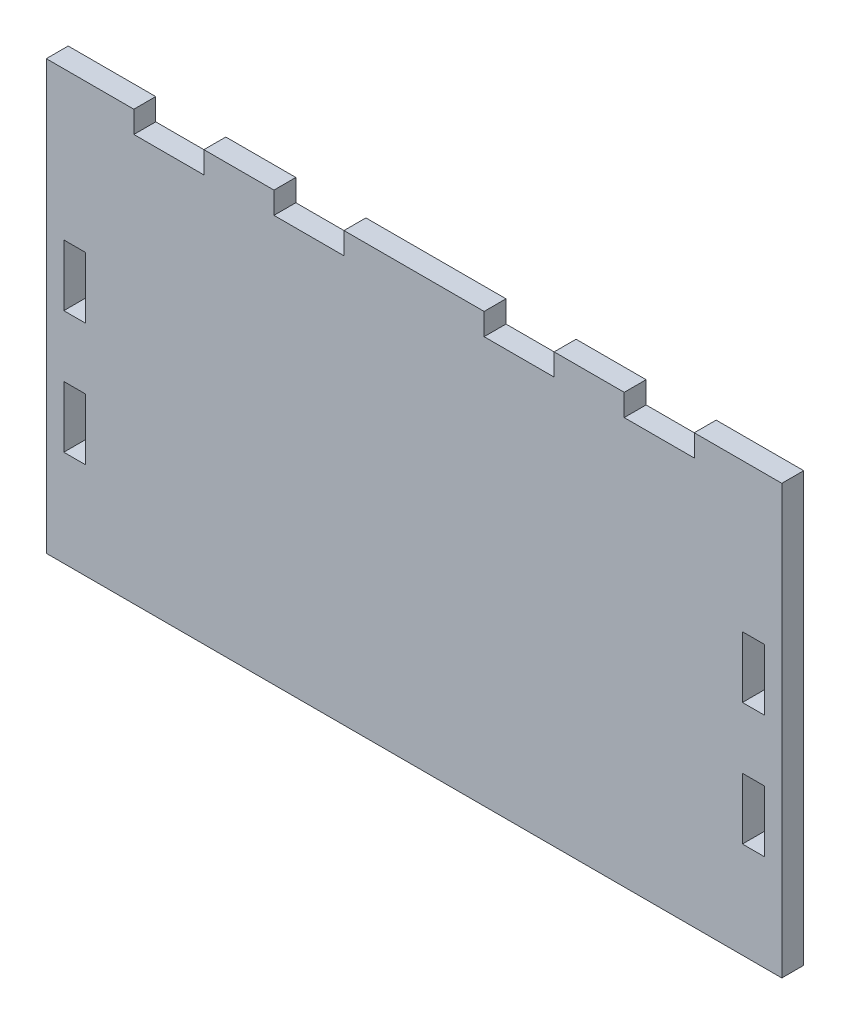
SolidWorks part; units mm, degrees
material "Beech"
ref_plane "Front" through (0, 0, 0) normal (0, 0, 1) x (1, 0, 0)
ref_plane "Top" through (0, 0, 0) normal (0, 1, 0) x (1, 0, 0)
ref_plane "Right" through (0, 0, 0) normal (1, 0, 0) x (0, 0, -1)
sketch "Sketch1" plane through (0, 0, 0) normal (0, 0, 1) x (1, 0, 0)
  line L0 (-42, -24.4632) -> (0, -24.4632) construction
  line L1 (-42, -24.4632) -> (-42, 24.4632) construction
  line L2 (0, -24.4632) -> (0, 24.4632) construction
  line L3 (-42, 24.4632) -> (0, 24.4632) construction
  line L4 (-42, -24.4632) -> (0, 24.4632) construction
  line L5 (0, -24.4632) -> (-42, 24.4632) construction
  line L6 (-42, 21.9632) -> (0, 21.9632) construction
  line L7 (-3.222, 0) -> (6.3832, 0) construction
  line L10 (-16, 21.9632) -> (-16, 24.4632)
  line L18 (-32, 21.9632) -> (-32, 24.4632)
  line L19 (-32, 24.4632) -> (-24, 24.4632) construction
  line L20 (-24, 21.9632) -> (-24, 24.4632)
  line L21 (-32, 21.9632) -> (-24, 24.4632) construction
  line L22 (-32, 24.4632) -> (-24, 21.9632) construction
  line L24 (-8, 21.9632) -> (-8, 24.4632)
  line L25 (-16, 24.4632) -> (-8, 24.4632) construction
  line L31 (-32, 21.9632) -> (-42, 21.9632) construction
  line L32 (-42, 21.9632) -> (-42, -24.4632)
  line L33 (-42, -24.4632) -> (42, -24.4632)
  line L35 (8, 21.9632) -> (-8, 21.9632) construction
  line L36 (-16, 21.9632) -> (-24, 21.9632) construction
  line L44 (42, 21.9632) -> (42, -24.4632)
  line L45 (32, 21.9632) -> (42, 21.9632) construction
  line L46 (32, 21.9632) -> (32, 24.4632)
  line L47 (32, 24.4632) -> (24, 24.4632) construction
  line L48 (24, 21.9632) -> (24, 24.4632)
  line L49 (16, 21.9632) -> (24, 21.9632) construction
  line L50 (16, 21.9632) -> (16, 24.4632)
  line L51 (16, 24.4632) -> (8, 24.4632) construction
  line L52 (8, 21.9632) -> (8, 24.4632)
  line L53 (-37.5, 0.5368) -> (-37.5, 7.5368)
  line L54 (-37.5, -13.4632) -> (-40, -13.4632)
  line L55 (-37.5, -13.4632) -> (-37.5, -6.4632)
  line L56 (-37.5, -6.4632) -> (-40, -6.4632)
  line L57 (-40, -13.4632) -> (-40, -6.4632)
  line L58 (-37.5, -13.4632) -> (-40, -6.4632) construction
  line L59 (-37.5, -6.4632) -> (-40, -13.4632) construction
  line L60 (-37.5, 0.5368) -> (-40, 0.5368)
  line L61 (-40, 0.5368) -> (-40, 7.5368)
  line L62 (-37.5, 7.5368) -> (-40, 7.5368)
  line L63 (37.5, -6.4632) -> (40, -6.4632)
  line L64 (40, -13.4632) -> (40, -6.4632)
  line L65 (37.5, -13.4632) -> (40, -13.4632)
  line L66 (37.5, -13.4632) -> (37.5, -6.4632)
  line L67 (37.5, 0.5368) -> (40, 0.5368)
  line L68 (40, 0.5368) -> (40, 7.5368)
  line L69 (37.5, 7.5368) -> (40, 7.5368)
  line L70 (37.5, 0.5368) -> (37.5, 7.5368)
  line L71 (42, 21.9632) -> (42, 24.4632)
  line L72 (42, 24.4632) -> (32, 24.4632)
  line L73 (32, 21.9632) -> (24, 21.9632)
  line L74 (24, 24.4632) -> (16, 24.4632)
  line L75 (16, 21.9632) -> (8, 21.9632)
  line L76 (8, 24.4632) -> (-8, 24.4632)
  line L77 (-8, 21.9632) -> (-16, 21.9632)
  line L78 (-16, 24.4632) -> (-24, 24.4632)
  line L79 (-24, 21.9632) -> (-32, 21.9632)
  line L80 (-32, 24.4632) -> (-42, 24.4632)
  line L81 (-42, 24.4632) -> (-42, 21.9632)
  point P1 (-21, 0)
  point P12 (0, 0)
  point P15 (0, 0)
  point P24 (-28, 23.2132)
  point P55 (-38.75, -9.9632)
  dimension "D1" = 2.5
  dimension "D2" = 42
  dimension "D3" = 48.9264
  dimension "D4" = 14.4264
  dimension "D6" = 10
  dimension "D7" = 8
  dimension "D10" = 8
  dimension "D11" = 7
  dimension "D12" = 2
  dimension "D13" = 2.5
  dimension "D16" = 7
  dimension "D8" = 2
  dimension "D15" = 2
extrude "Boss-Extrude1" add sketch "Sketch1" along normal blind 2.5
